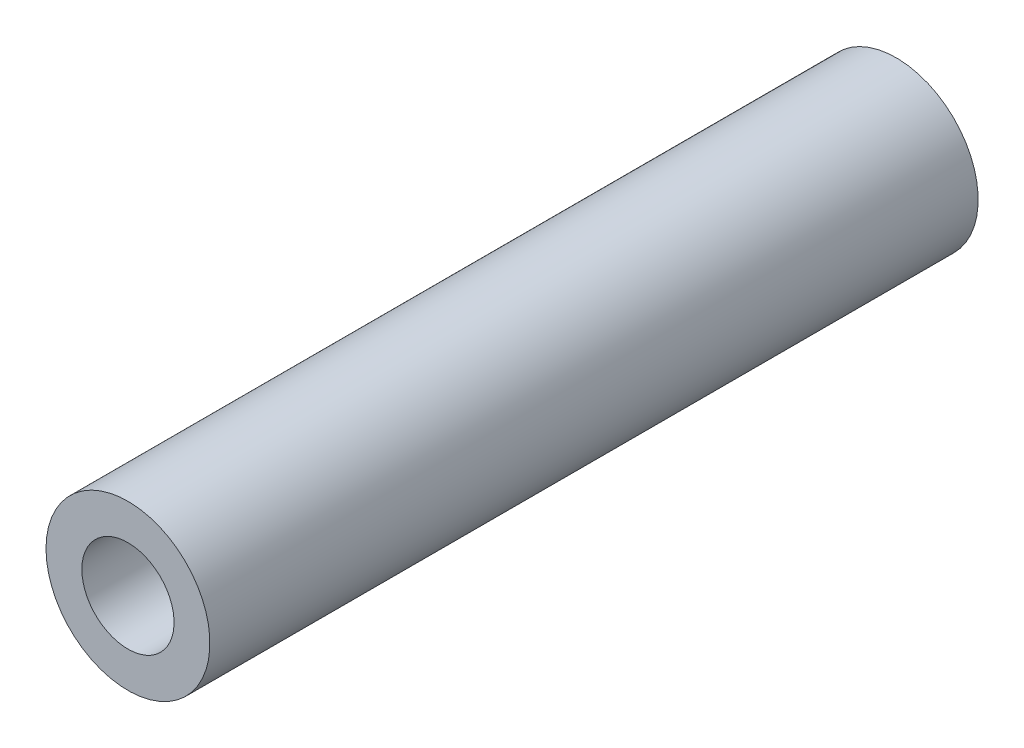
SolidWorks part; units mm, degrees
ref_plane "Front Plane" through (0, 0, 0) normal (0, 0, 1) x (1, 0, 0)
ref_plane "Top Plane" through (0, 0, 0) normal (0, 1, 0) x (1, 0, 0)
ref_plane "Right Plane" through (0, 0, 0) normal (1, 0, 0) x (0, 0, -1)
sketch "Sketch1" plane through (0, 0, 0) normal (0, 0, 1) x (1, 0, 0)
  circle A0 centre (0, 0) radius 4.8
  circle A1 centre (0, 0) radius 2.7
  dimension "D1" = 9.6
  dimension "D2" = 5.4
extrude "Boss-Extrude1" add sketch "Sketch1" along normal blind 45 contours A0 A1
